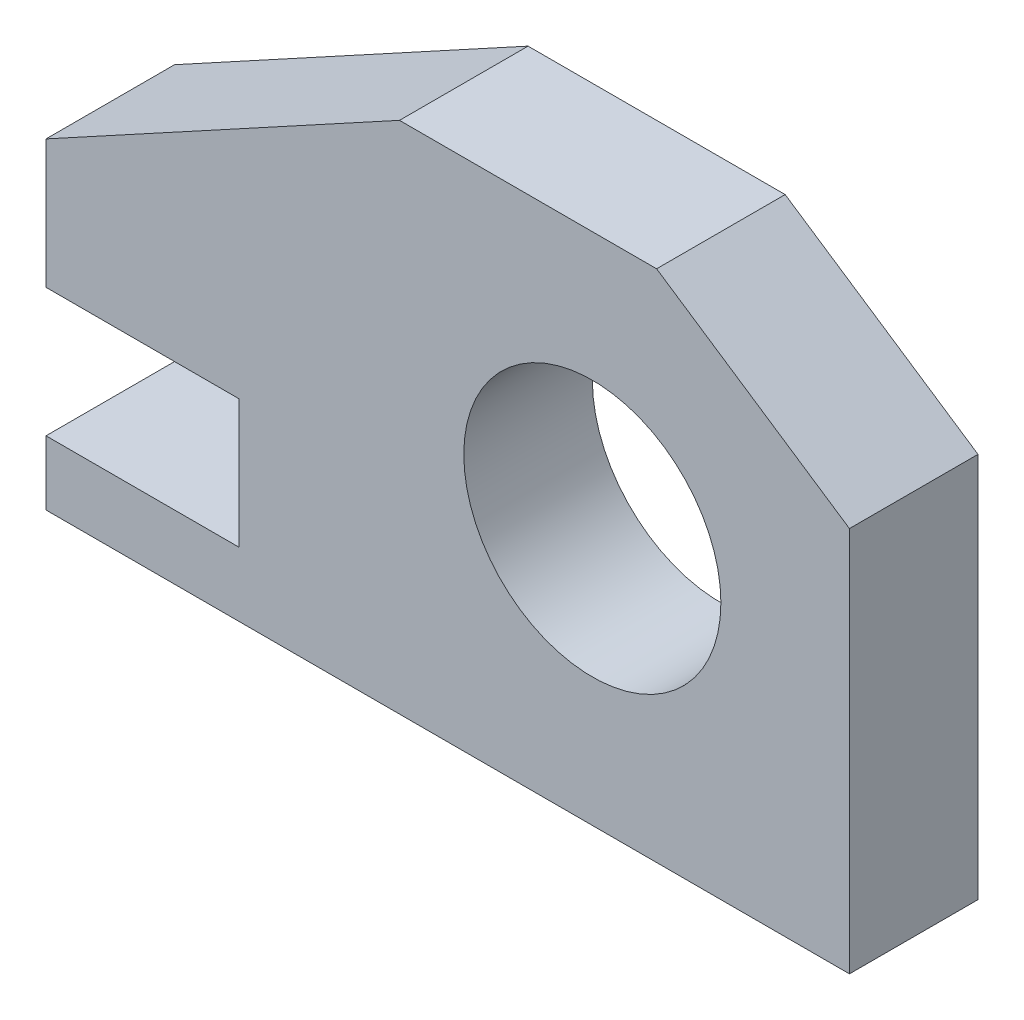
SolidWorks part; units mm, degrees
ref_plane "Front Plane" through (0, 0, 0) normal (0, 0, 1) x (1, 0, 0)
ref_plane "Top Plane" through (0, 0, 0) normal (0, 1, 0) x (1, 0, 0)
ref_plane "Right Plane" through (0, 0, 0) normal (1, 0, 0) x (0, 0, -1)
sketch "Sketch1" plane through (0, 0, 0) normal (0, 0, 1) x (1, 0, 0)
  line L0 (60.3235, 50.8) -> (79.3735, 38.1)
  line L1 (0, 0) -> (79.3735, 0)
  line L2 (0, 0) -> (0, 50.8)
  line L3 (0, 50.8) -> (79.3735, 50.8)
  line L4 (79.3735, 0) -> (79.3735, 50.8)
  line L5 (0, 6.35) -> (19.05, 6.35)
  line L6 (0, 6.35) -> (0, 19.05)
  line L7 (0, 19.05) -> (19.05, 19.05)
  line L8 (19.05, 6.35) -> (19.05, 19.05)
  line L9 (0, 31.75) -> (34.9235, 50.8)
  circle A0 centre (53.9735, 25.4) radius 12.7
  dimension "D10" = 25.4
  dimension "D1" = 12.7
  dimension "D2" = 19.05
  dimension "D3" = 6.35
  dimension "D4" = 31.75
  dimension "D5" = 50.8
  dimension "D6" = 19.05
  dimension "D7" = 25.4
  dimension "D8" = 25.4
  dimension "D9" = 25.4
  dimension "D11" = 38.1
extrude "Boss-Extrude1" add sketch "Sketch1" along normal blind 12.7 contours L9 L2 L7 L8 L5 L1 L4 L0 L3 A0
